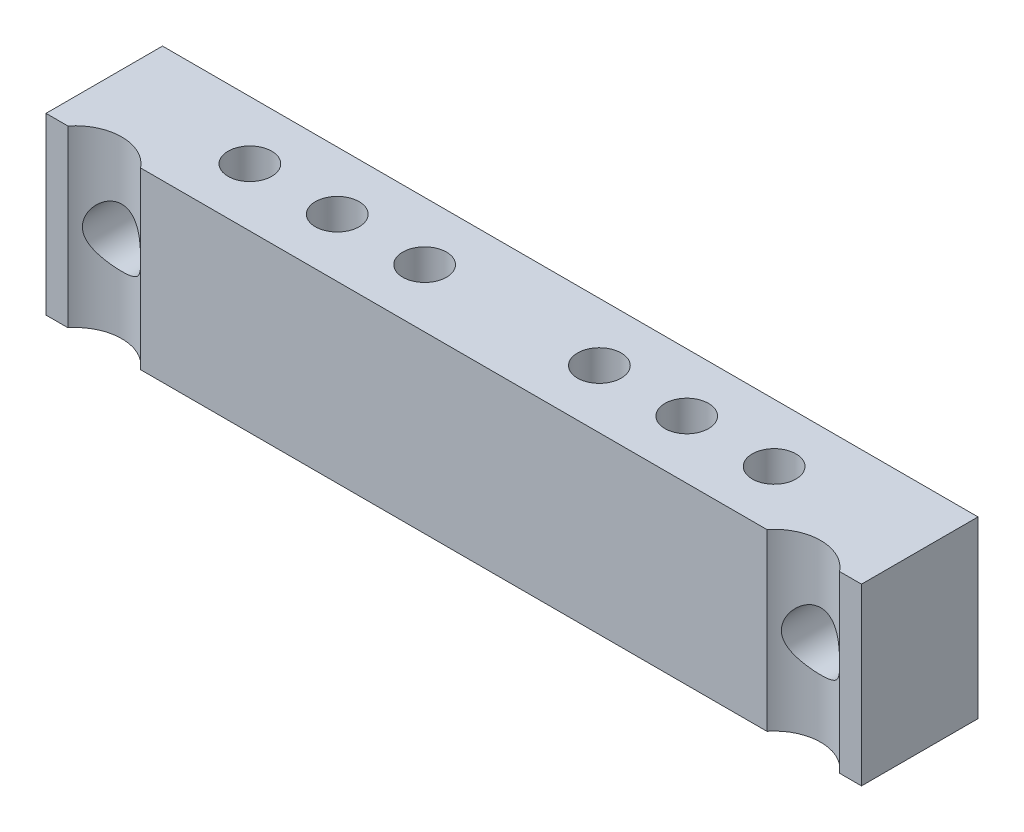
SolidWorks part; units mm, degrees
material "Aleación 1060"
ref_plane "Alzado" through (0, 0, 0) normal (0, 0, 1) x (1, 0, 0)
ref_plane "Planta" through (0, 0, 0) normal (0, 1, 0) x (1, 0, 0)
ref_plane "Vista lateral" through (0, 0, 0) normal (1, 0, 0) x (0, 0, -1)
sketch "Croquis1" plane through (0, 0, 0) normal (0, 0, 1) x (1, 0, 0)
  line L0 (14, 6) -> (14, 0) construction
  line L1 (0, 0) -> (28, 0)
  line L2 (0, 0) -> (0, 6)
  line L3 (0, 6) -> (28, 6)
  line L4 (28, 0) -> (28, 6)
  circle A0 centre (2, 3) radius 1
  circle A1 centre (26, 3) radius 1
  dimension "D3" = 2
  dimension "D5" = 3
  dimension "D1" = 28
  dimension "D2" = 6
  dimension "D4" = 2
extrude "Saliente-Extruir1" add sketch "Croquis1" along normal blind 4
sketch "Croquis2" plane through (0, 0, 0) normal (0, -1, 0) x (1, 0, 0)
  line L0 (0, 4) -> (28, 4) construction
  line L1 (14, 4) -> (14, 0) construction
  line L2 (0, 0) -> (28, 0) construction
  circle A0 centre (2, 5) radius 1.6
  circle A1 centre (11, 2) radius 0.75
  circle A2 centre (8, 2) radius 0.75
  circle A3 centre (5, 2) radius 0.75
  circle A4 centre (23, 2) radius 0.75
  circle A5 centre (20, 2) radius 0.75
  circle A6 centre (17, 2) radius 0.75
  circle A7 centre (26, 5) radius 1.6
  dimension "D1" = 1
  dimension "D2" = 2
  dimension "D3" = 3
  dimension "D4" = 1.5
  dimension "D5" = 3
extrude "Cortar-Extruir1" cut sketch "Croquis2" against normal up to vertex (6 mm away)
